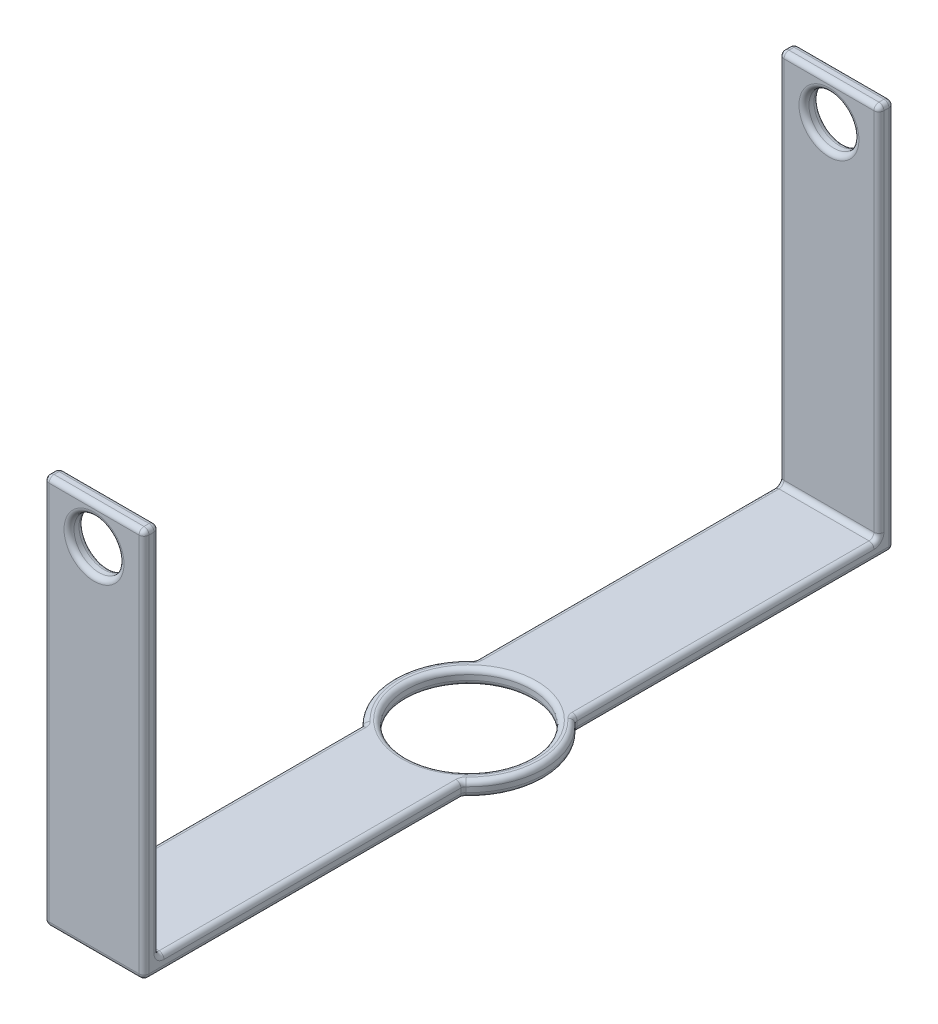
SolidWorks part; units mm, degrees
material "Custom Plastic"
ref_plane "Front Plane" through (0, 0, 0) normal (0, 0, 1) x (1, 0, 0)
ref_plane "Top Plane" through (0, 0, 0) normal (0, 1, 0) x (1, 0, 0)
ref_plane "Right Plane" through (0, 0, 0) normal (1, 0, 0) x (0, 0, -1)
sketch "Sketch1" plane through (0, 0, 0) normal (0, 1, 0) x (1, 0, 0)
  line L1 (-63.3526, 44.9422) -> (-43.3526, 44.9422)
  line L2 (-63.3526, 44.9422) -> (-63.3526, -105.0578)
  line L3 (-63.3526, -105.0578) -> (-43.3526, -105.0578)
  line L4 (-43.3526, 44.9422) -> (-43.3526, -105.0578)
  dimension "D1" = 150
  dimension "D2" = 20
extrude "Boss-Extrude1" add sketch "Sketch1" along normal blind 3
sketch "Sketch2" plane through (0, 3, 0) normal (0, 1, 0) x (1, 0, 0)
  line L0 (-43.3526, -105.0578) -> (-43.3526, 44.9422) construction
  line L1 (-63.3526, 44.9422) -> (-43.3526, 44.9422)
  line L2 (-63.3526, 44.9422) -> (-63.3526, 41.9422)
  line L3 (-63.3526, 41.9422) -> (-43.3526, 41.9422)
  line L4 (-43.3526, 44.9422) -> (-43.3526, 41.9422)
  line L6 (-63.3526, -105.0578) -> (-43.3526, -105.0578)
  line L7 (-63.3526, -105.0578) -> (-63.3526, -102.0578)
  line L8 (-63.3526, -102.0578) -> (-43.3526, -102.0578)
  line L9 (-43.3526, -105.0578) -> (-43.3526, -102.0578)
  dimension "D1" = 3
  dimension "D2" = 3
extrude "Boss-Extrude2" add sketch "Sketch2" along normal blind 75
sketch "Sketch4" plane through (0, 0, -44.9422) normal (0, 0, -1) x (-1, 0, 0)
  line L0 (43.3526, 78) -> (63.3526, 78) construction
  circle A0 centre (53.3526, 70.5) radius 5
  point P4 (53.3526, 78)
  dimension "D1" = 7.5
extrude "Cut-Extrude1" cut sketch "Sketch4" against normal through all
sketch "Sketch5" plane through (0, 3, 0) normal (0, 1, 0) x (1, 0, 0)
  circle A0 centre (-53.3526, -30.0578) radius 15
extrude "Boss-Extrude3" add sketch "Sketch5" against normal blind 3
sketch "Sketch6" plane through (0, 3, 0) normal (0, 1, 0) x (1, 0, 0)
  circle A0 centre (-53.3526, -30.0578) radius 12.5
extrude "Cut-Extrude2" cut sketch "Sketch6" against normal through all
fillet "Fillet1" radius 1 42 edges at (-63.3526, 3, -11.5324) (-43.3526, 3, 71.648) (-53.3526, 3, -41.9422) (-63.3526, 40.5, -41.9422) (-43.3526, 40.5, -41.9422) (-63.3526, 78, -43.4422) (-53.3526, 78, -41.9422) (-43.3526, 78, -43.4422) (-53.3526, 78, -44.9422) (-63.3526, 40.5, 102.0578) (-53.3526, 3, 102.0578) (-43.3526, 40.5, 102.0578) (-63.3526, 78, 103.5578) (-53.3526, 78, 105.0578) (-43.3526, 78, 103.5578) (-53.3526, 78, 102.0578) (-58.3526, 70.5, 105.0578) (-48.3526, 70.5, 102.0578) (-58.3526, 70.5, -41.9422) (-58.3526, 70.5, -44.9422) (-63.3526, 0, 73.148) (-43.3526, 0, -13.0324) (-53.3526, 0, -44.9422) (-63.3526, 3, 71.648) (-43.3526, 3, -11.5324) (-43.3526, 0, 73.148) (-68.3526, 3, 30.0578) (-38.3526, 3, 30.0578) (-68.3526, 0, 30.0578) (-63.3526, 1.5, 18.8775) (-43.3526, 1.5, 18.8775) (-38.3526, 0, 30.0578) (-53.3526, 0, 105.0578) (-63.3526, 1.5, 41.2381) (-43.3526, 1.5, 41.2381) (-63.3526, 0, -13.0324) (-53.3526, 0, 42.5578) (-53.3526, 3, 42.5578) (-63.3526, 39, -44.9422) (-43.3526, 39, -44.9422) (-43.3526, 39, 105.0578) (-63.3526, 39, 105.0578)
